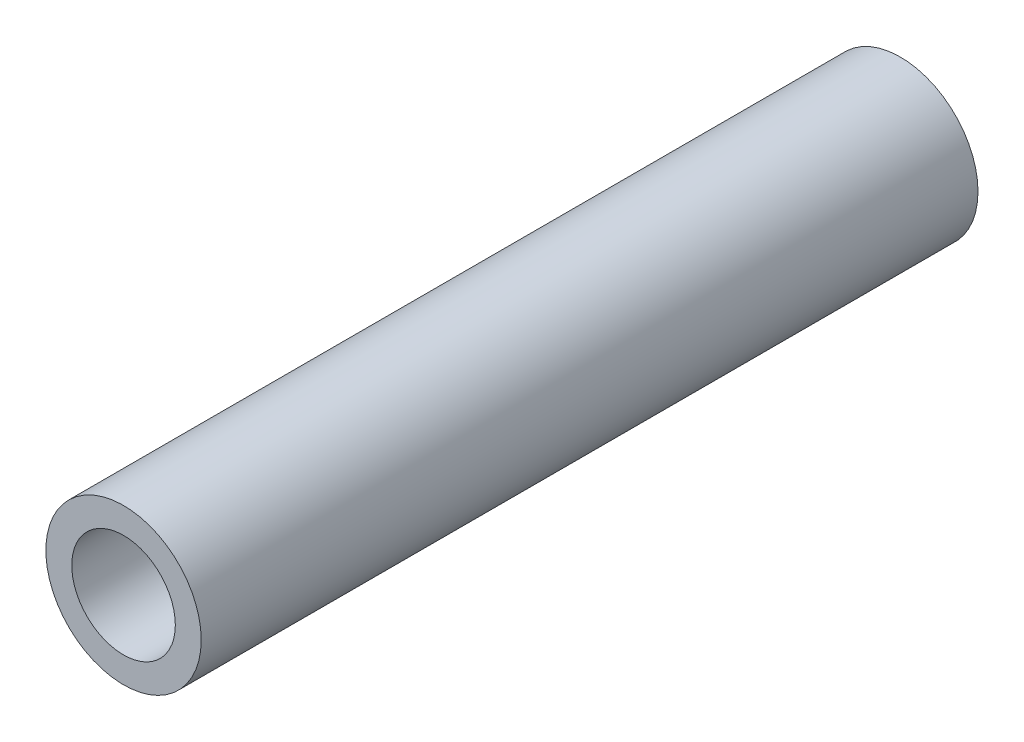
SolidWorks part; units mm, degrees
ref_plane "Front Plane" through (0, 0, 0) normal (0, 0, 1) x (1, 0, 0)
ref_plane "Top Plane" through (0, 0, 0) normal (0, 1, 0) x (1, 0, 0)
ref_plane "Right Plane" through (0, 0, 0) normal (1, 0, 0) x (0, 0, -1)
sketch "Sketch1" plane through (0, 0, 0) normal (0, 0, 1) x (1, 0, 0)
  circle A0 centre (0, 0) radius 3
  circle A1 centre (0, 0) radius 2
  dimension "D1" = 6
  dimension "D2" = 1
extrude "Boss-Extrude1" add sketch "Sketch1" along normal blind 30
